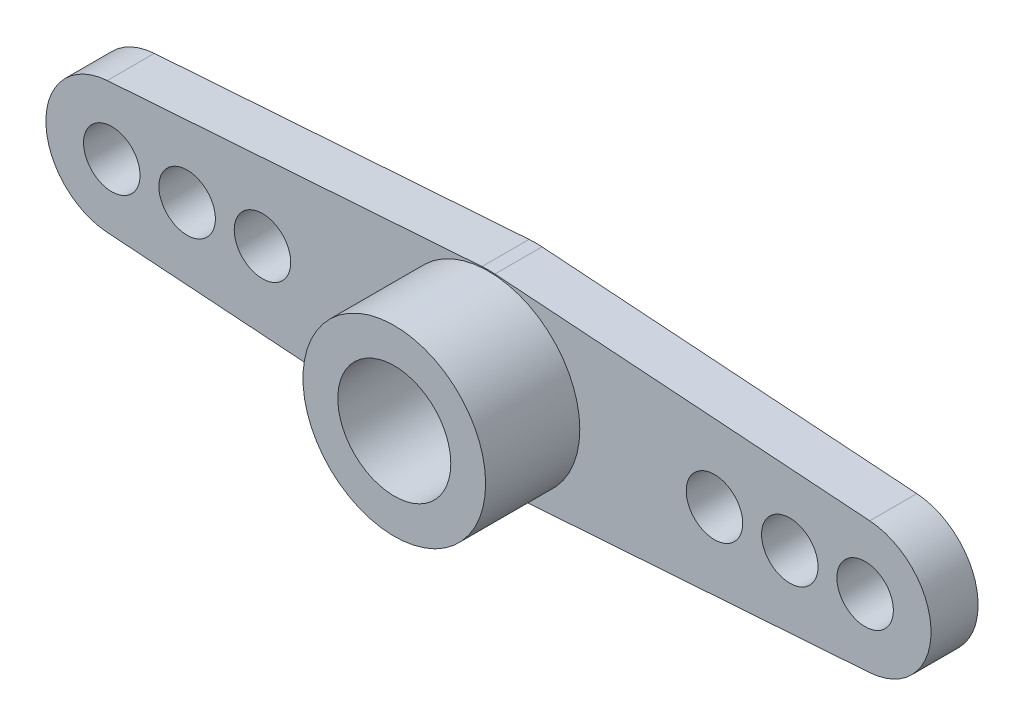
SolidWorks part; units mm, degrees
ref_plane "前视基准面" through (0, 0, 0) normal (0, 0, 1) x (1, 0, 0)
ref_plane "上视基准面" through (0, 0, 0) normal (0, 1, 0) x (1, 0, 0)
ref_plane "右视基准面" through (0, 0, 0) normal (1, 0, 0) x (0, 0, -1)
sketch "草图1" plane through (0, 0, 0) normal (0, 0, 1) x (1, 0, 0)
  line L0 (-20, 0) -> (20, 0) construction
  line L1 (0, 0) -> (0, 25.4851) construction
  line L2 (-0.343, -4.888) -> (-20.245, -3.4914)
  line L3 (0.343, 4.888) -> (20.245, 3.4914)
  line L4 (0.343, -4.888) -> (20.245, -3.4914)
  line L5 (-0.343, 4.888) -> (-20.245, 3.4914)
  circle A0 centre (20, 0) radius 1.5
  circle A1 centre (16, 0) radius 1.5
  circle A2 centre (12, 0) radius 1.5
  circle A3 centre (0, 0) radius 3
  circle A4 centre (-12, 0) radius 1.5
  circle A5 centre (-16, 0) radius 1.5
  circle A6 centre (-20, 0) radius 1.5
  arc A7 (20.245, -3.4914) -> (20.245, 3.4914) centre (20, 0) ccw
  arc A8 (-0.343, -4.888) -> (0.343, -4.888) centre (0, 0) ccw
  arc A9 (-20.245, -3.4914) -> (-20.245, 3.4914) centre (-20, 0) cw
  arc A10 (0.343, 4.888) -> (-0.343, 4.888) centre (0, 0) ccw
  point P4 (0, 0)
  dimension "D2" = 3
  dimension "D3" = 3
  dimension "D4" = 4
  dimension "D5" = 3
  dimension "D6" = 4
  dimension "D7" = 6
  dimension "D9" = 9.8
  dimension "D1" = 40
extrude "凸台-拉伸1" add sketch "草图1" along normal blind 2.5
sketch "草图2" plane through (0, 0, 2.5) normal (0, 0, 1) x (1, 0, 0)
  circle A0 centre (0, 0) radius 3
  circle A1 centre (0, 0) radius 4.85
  dimension "D1" = 9.7
extrude "凸台-拉伸2" add sketch "草图2" along normal blind 5
